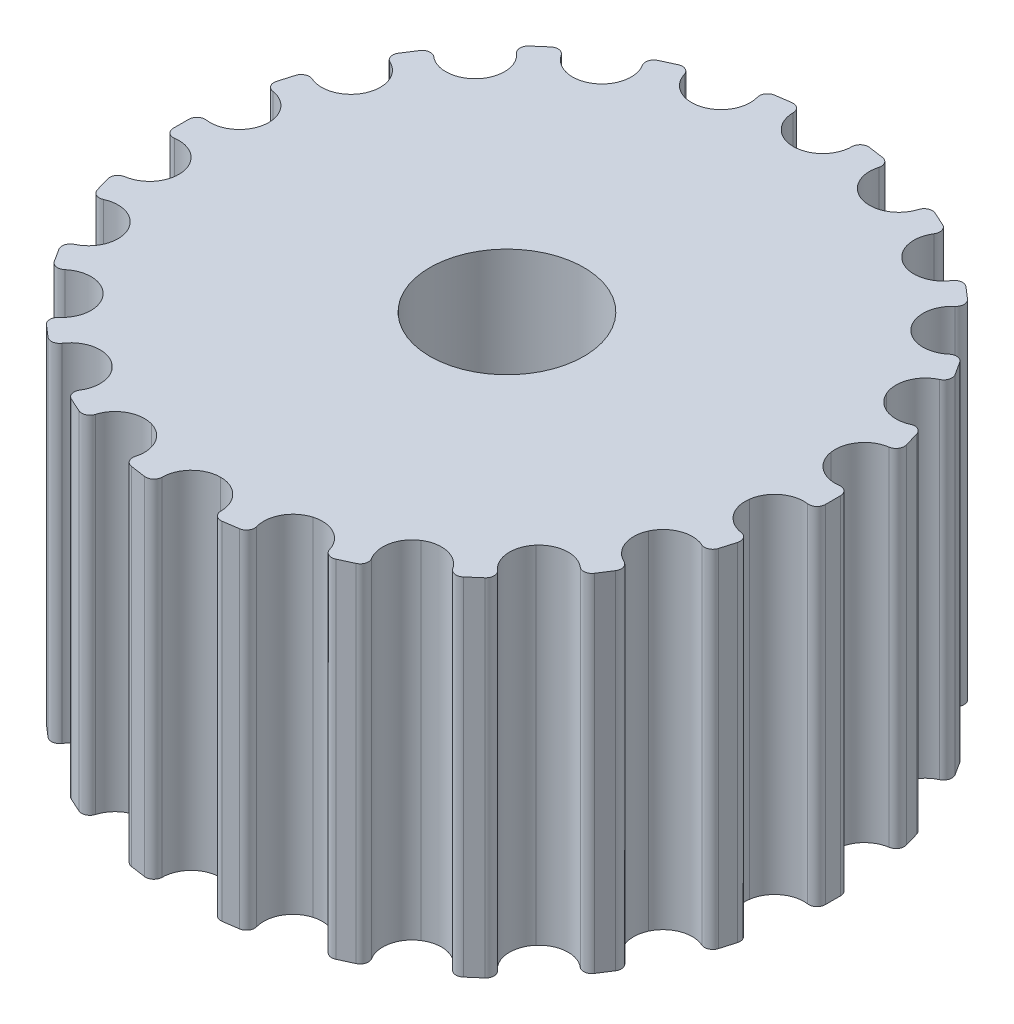
SolidWorks part; units mm, degrees
ref_plane "Ebene vorne" through (0, 0, 0) normal (0, 0, 1) x (1, 0, 0)
ref_plane "Ebene oben" through (0, 0, 0) normal (0, 1, 0) x (1, 0, 0)
ref_plane "Ebene rechts" through (0, 0, 0) normal (1, 0, 0) x (0, 0, -1)
sketch "Skizze1" plane through (0, 0, 0) normal (0, 1, 0) x (1, 0, 0)
  line L0 (0, 0) -> (-50000, 0) construction
  line L1 (0, 0) -> (5.7186, 19.4803) construction
  line L2 (0, 0) -> (0, 50000) construction
  line L3 (2.0161, 16.8144) -> (2.8016, 16.7015)
  line L4 (6.6707, 15.5656) -> (7.3926, 15.2359)
  line L5 (10.785, 13.056) -> (11.3847, 12.5363)
  line L6 (14.0255, 9.4889) -> (14.4545, 8.8213)
  line L7 (16.1298, 5.1534) -> (16.3534, 4.3919)
  line L8 (16.9274, 0.4006) -> (16.9274, -0.393)
  line L9 (16.3536, -4.3844) -> (16.1301, -5.1458)
  line L10 (14.4551, -8.8139) -> (14.0261, -9.4815)
  line L11 (11.3855, -12.529) -> (10.7858, -13.0487)
  line L12 (7.3935, -15.2289) -> (6.6717, -15.5586)
  line L13 (2.8027, -16.6948) -> (2.0172, -16.8077)
  line L14 (-2.0152, -16.8079) -> (-2.8007, -16.695)
  line L15 (-6.6698, -15.559) -> (-7.3917, -15.2294)
  line L16 (-10.784, -13.0494) -> (-11.3838, -12.5297)
  line L17 (-14.0246, -9.4823) -> (-14.4536, -8.8148)
  line L18 (-16.1289, -5.1468) -> (-16.3524, -4.3854)
  line L19 (-16.9264, -0.394) -> (-16.9265, 0.3995)
  line L20 (-16.3527, 4.3909) -> (-16.1292, 5.1524)
  line L21 (-14.4542, 8.8204) -> (-14.0251, 9.488)
  line L22 (-11.3846, 12.5356) -> (-10.7849, 13.0553)
  line L23 (-7.3926, 15.2355) -> (-6.6708, 15.5652)
  line L24 (-2.8017, 16.7014) -> (-2.0163, 16.8143)
  circle A0 centre (0, 0) radius 16.935 construction
  arc A2 (0, 14.875) -> (1.525, 16.3913) centre (0, 16.4) ccw
  arc A3 (2.0161, 16.8144) -> (1.525, 16.3913) centre (1.955, 16.3888) ccw
  arc A4 (3.1537, 16.1571) -> (4.1899, 14.2727) centre (4.6194, 15.736) ccw
  arc A5 (3.1537, 16.1571) -> (2.8016, 16.7015) centre (2.7405, 16.2759) ccw
  arc A6 (4.1899, 14.2727) -> (6.0803, 15.2979) centre (4.6195, 15.7359) ccw
  arc A7 (6.6707, 15.5656) -> (6.0803, 15.2979) centre (6.4921, 15.1744) ccw
  arc A8 (7.5771, 14.6144) -> (8.0403, 12.5144) centre (8.8647, 13.7974) ccw
  arc A9 (7.5771, 14.6144) -> (7.3926, 15.2359) centre (7.214, 14.8448) ccw
  arc A10 (8.0403, 12.5144) -> (10.143, 12.9655) centre (8.8648, 13.7973) ccw
  arc A11 (10.785, 13.056) -> (10.143, 12.9655) centre (10.5034, 12.731) ccw
  arc A12 (11.3866, 11.888) -> (11.2395, 9.7425) centre (12.3919, 10.7413) ccw
  arc A13 (11.3866, 11.888) -> (11.3847, 12.5363) centre (11.1031, 12.2113) ccw
  arc A14 (11.2395, 9.7425) -> (13.384, 9.583) centre (12.392, 10.7412) ccw
  arc A15 (14.0255, 9.4889) -> (13.384, 9.583) centre (13.6637, 9.2564) ccw
  arc A16 (14.2737, 8.1987) -> (13.5281, 6.1816) centre (14.9152, 6.8152) ccw
  arc A17 (14.2737, 8.1987) -> (14.4545, 8.8213) centre (14.0928, 8.5888) ccw
  arc A18 (13.5281, 6.1816) -> (15.5408, 5.4244) centre (14.9152, 6.8151) ccw
  arc A19 (16.1298, 5.1534) -> (15.5408, 5.4244) centre (15.7172, 5.0322) ccw
  arc A20 (16.0044, 3.8455) -> (14.7207, 2.1202) centre (16.2302, 2.3373) ccw
  arc A21 (16.0044, 3.8455) -> (16.3534, 4.3919) centre (15.9408, 4.2708) ccw
  arc A22 (14.7207, 2.1202) -> (16.4386, 0.8265) centre (16.2302, 2.3372) ccw
  arc A23 (16.9274, 0.4006) -> (16.4386, 0.8265) centre (16.4974, 0.4006) ccw
  arc A24 (16.4387, -0.819) -> (14.7209, -2.1127) centre (16.2304, -2.3297) ccw
  arc A25 (16.4387, -0.819) -> (16.9274, -0.393) centre (16.4974, -0.393) ccw
  arc A26 (14.7209, -2.1127) -> (16.0047, -3.838) centre (16.2303, -2.3298) ccw
  arc A27 (16.3536, -4.3844) -> (16.0047, -3.838) centre (15.941, -4.2632) ccw
  arc A28 (15.5411, -5.4168) -> (13.5284, -6.1742) centre (14.9157, -6.8077) ccw
  arc A29 (15.5411, -5.4168) -> (16.1301, -5.1458) centre (15.7175, -5.0247) ccw
  arc A30 (13.5284, -6.1742) -> (14.2742, -8.1913) centre (14.9156, -6.8077) ccw
  arc A31 (14.4551, -8.8139) -> (14.2742, -8.1913) centre (14.0933, -8.5814) ccw
  arc A32 (13.3846, -9.5756) -> (11.2401, -9.7353) centre (12.3926, -10.7339) ccw
  arc A33 (13.3846, -9.5756) -> (14.0261, -9.4815) centre (13.6643, -9.249) ccw
  arc A34 (11.2401, -9.7353) -> (11.3873, -11.8807) centre (12.3926, -10.7339) ccw
  arc A35 (11.3855, -12.529) -> (11.3873, -11.8807) centre (11.1039, -12.2041) ccw
  arc A36 (10.1438, -12.9583) -> (8.0411, -12.5074) centre (8.8657, -13.7902) ccw
  arc A37 (10.1438, -12.9583) -> (10.7858, -13.0487) centre (10.5042, -12.7238) ccw
  arc A38 (8.0411, -12.5074) -> (7.578, -14.6074) centre (8.8656, -13.7903) ccw
  arc A39 (7.3935, -15.2289) -> (7.578, -14.6074) centre (7.2149, -14.8378) ccw
  arc A40 (6.0812, -15.291) -> (4.1907, -14.2659) centre (4.6205, -15.7291) ccw
  arc A41 (6.0812, -15.291) -> (6.6717, -15.5586) centre (6.4931, -15.1675) ccw
  arc A42 (4.1907, -14.2659) -> (3.1547, -16.1504) centre (4.6204, -15.7291) ccw
  arc A43 (2.8027, -16.6948) -> (3.1547, -16.1504) centre (2.7415, -16.2692) ccw
  arc A44 (1.526, -16.3846) -> (0.0009, -14.8684) centre (0.001, -16.3934) ccw
  arc A45 (1.526, -16.3846) -> (2.0172, -16.8077) centre (1.956, -16.3821) ccw
  arc A46 (0.0009, -14.8684) -> (-1.5241, -16.3847) centre (0.0009, -16.3934) ccw
  arc A47 (-2.0152, -16.8079) -> (-1.5241, -16.3847) centre (-1.954, -16.3822) ccw
  arc A48 (-3.1528, -16.1506) -> (-4.1889, -14.2662) centre (-4.6185, -15.7294) ccw
  arc A49 (-3.1528, -16.1506) -> (-2.8007, -16.695) centre (-2.7395, -16.2693) ccw
  arc A50 (-4.1889, -14.2662) -> (-6.0793, -15.2914) centre (-4.6186, -15.7294) ccw
  arc A51 (-6.6698, -15.559) -> (-6.0793, -15.2914) centre (-6.4912, -15.1679) ccw
  arc A52 (-7.5761, -14.6079) -> (-8.0394, -12.5078) centre (-8.8638, -13.7908) ccw
  arc A53 (-7.5761, -14.6079) -> (-7.3917, -15.2294) centre (-7.2131, -14.8382) ccw
  arc A54 (-8.0394, -12.5078) -> (-10.1421, -12.959) centre (-8.8639, -13.7908) ccw
  arc A55 (-10.784, -13.0494) -> (-10.1421, -12.959) centre (-10.5025, -12.7244) ccw
  arc A56 (-11.3857, -11.8814) -> (-11.2385, -9.736) centre (-12.391, -10.7347) ccw
  arc A57 (-11.3857, -11.8814) -> (-11.3838, -12.5297) centre (-11.1022, -12.2048) ccw
  arc A58 (-11.2385, -9.736) -> (-13.3831, -9.5764) centre (-12.3911, -10.7346) ccw
  arc A59 (-14.0246, -9.4823) -> (-13.3831, -9.5764) centre (-13.6628, -9.2498) ccw
  arc A60 (-14.2728, -8.1922) -> (-13.5271, -6.1751) centre (-14.9143, -6.8087) ccw
  arc A61 (-14.2728, -8.1922) -> (-14.4536, -8.8148) centre (-14.0919, -8.5823) ccw
  arc A62 (-13.5271, -6.1751) -> (-15.5399, -5.4178) centre (-14.9143, -6.8086) ccw
  arc A63 (-16.1289, -5.1468) -> (-15.5399, -5.4178) centre (-15.7163, -5.0256) ccw
  arc A64 (-16.0035, -3.839) -> (-14.7198, -2.1136) centre (-16.2293, -2.3308) ccw
  arc A65 (-16.0035, -3.839) -> (-16.3524, -4.3854) centre (-15.9399, -4.2642) ccw
  arc A66 (-14.7198, -2.1136) -> (-16.4377, -0.82) centre (-16.2293, -2.3307) ccw
  arc A67 (-16.9264, -0.394) -> (-16.4377, -0.82) centre (-16.4964, -0.394) ccw
  arc A68 (-16.4377, 0.8255) -> (-14.72, 2.1193) centre (-16.2294, 2.3362) ccw
  arc A69 (-16.4377, 0.8255) -> (-16.9265, 0.3995) centre (-16.4965, 0.3996) ccw
  arc A70 (-14.72, 2.1193) -> (-16.0038, 3.8445) centre (-16.2294, 2.3363) ccw
  arc A71 (-16.3527, 4.3909) -> (-16.0038, 3.8445) centre (-15.9401, 4.2698) ccw
  arc A72 (-15.5402, 5.4234) -> (-13.5275, 6.1808) centre (-14.9148, 6.8142) ccw
  arc A73 (-15.5402, 5.4234) -> (-16.1292, 5.1524) centre (-15.7166, 5.0312) ccw
  arc A74 (-13.5275, 6.1808) -> (-14.2733, 8.1978) centre (-14.9147, 6.8143) ccw
  arc A75 (-14.4542, 8.8204) -> (-14.2733, 8.1978) centre (-14.0924, 8.588) ccw
  arc A76 (-13.3837, 9.5822) -> (-11.2391, 9.7418) centre (-12.3917, 10.7404) ccw
  arc A77 (-13.3837, 9.5822) -> (-14.0251, 9.488) centre (-13.6634, 9.2556) ccw
  arc A78 (-11.2391, 9.7418) -> (-11.3864, 11.8873) centre (-12.3917, 10.7405) ccw
  arc A79 (-11.3846, 12.5356) -> (-11.3864, 11.8873) centre (-11.103, 12.2106) ccw
  arc A80 (-10.1429, 12.9649) -> (-8.0402, 12.5139) centre (-8.8647, 13.7968) ccw
  arc A81 (-10.1429, 12.9649) -> (-10.7849, 13.0553) centre (-10.5033, 12.7303) ccw
  arc A82 (-8.0402, 12.5139) -> (-7.5771, 14.614) centre (-8.8647, 13.7968) ccw
  arc A83 (-7.3926, 15.2355) -> (-7.5771, 14.614) centre (-7.214, 14.8444) ccw
  arc A84 (-6.0803, 15.2976) -> (-4.1898, 14.2725) centre (-4.6196, 15.7357) ccw
  arc A85 (-6.0803, 15.2976) -> (-6.6708, 15.5652) centre (-6.4922, 15.174) ccw
  arc A86 (-4.1898, 14.2725) -> (-3.1538, 16.1569) centre (-4.6195, 15.7357) ccw
  arc A87 (-2.8017, 16.7014) -> (-3.1538, 16.1569) centre (-2.7405, 16.2757) ccw
  arc A88 (-1.5251, 16.3912) -> (0, 14.875) centre (-0.0001, 16.4) ccw
  arc A89 (-1.5251, 16.3912) -> (-2.0163, 16.8143) centre (-1.9551, 16.3887) ccw
  point P3 (4.1899, 14.2727)
  point P232 (0.0005, 0.0033)
  dimension "D1" = 33.87
  dimension "D3" = 3.05
  dimension "D4" = 0.86
  dimension "D5" = 73.64
  dimension "D6" = 22
extrude "Aufsatz-Linear austragen1" add sketch "Skizze1" along normal blind 18
hole_wizard "Ø8.0 (8) Durchmesser Bohrung1" positions "Skizze2" profile "Skizze3" hole size "Ø8.0" standard "ISO" end condition through all
sketch "Skizze2" plane through (0, 18, 0) normal (0, 1, 0) x (1, 0, 0)
  point P0 (0, 0)
sketch "Skizze3" plane through (0, 18, 0) normal (1, 0, 0) x (0, 0, 1)
  line L0 (0, 0) -> (0, 18)
  line L1 (0, 18) -> (4, 18)
  line L2 (4, 18) -> (4, 0)
  line L5 (4, 0) -> (0, 0)
  line L11 (0, -6.35) -> (0, 107.95) construction
  dimension "Bohrerdurchmesser" = 8
  dimension "Bohrungstiefe" = 18
